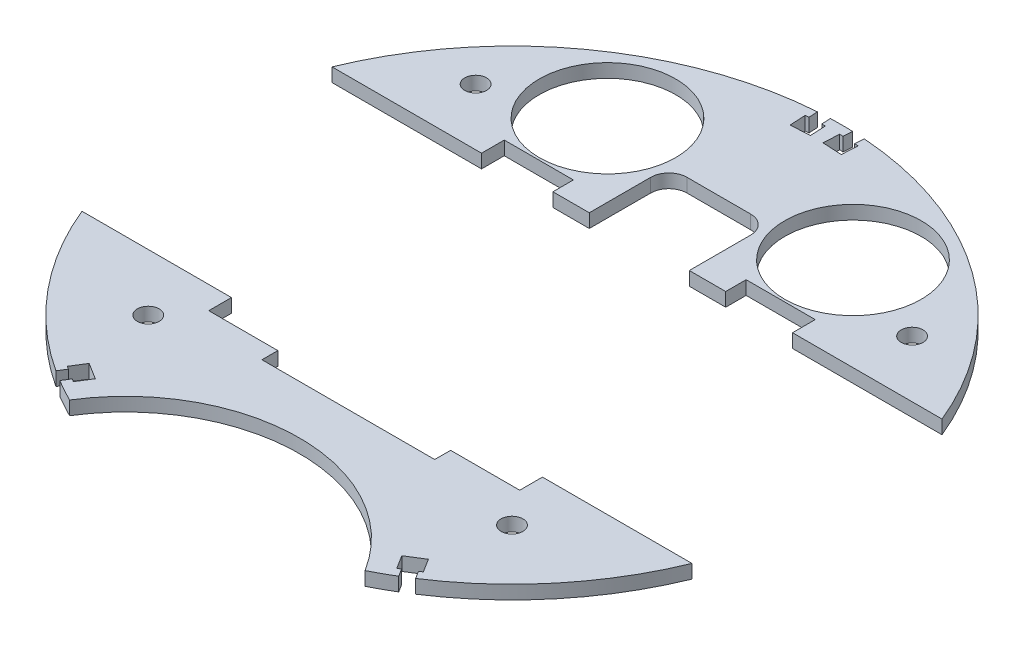
SolidWorks part; units mm, degrees
material "ABS"
ref_plane "Front Plane" through (0, 0, 0) normal (0, 0, 1) x (1, 0, 0)
ref_plane "Top Plane" through (0, 0, 0) normal (0, 1, 0) x (1, 0, 0)
ref_plane "Right Plane" through (0, 0, 0) normal (1, 0, 0) x (0, 0, -1)
sketch "Sketch1" plane through (0, 0, 0) normal (0, 1, 0) x (1, 0, 0)
  line L0 (0, -85) -> (-32.4891, -64.8129) construction
  line L1 (0, -85) -> (0, 0) construction
  arc A0 (32.4891, -64.8129) -> (-32.4891, -64.8129) centre (0, 0) ccw
  arc A1 (32.4891, -64.8129) -> (-32.4891, -64.8129) centre (0, -85) ccw
  dimension "D1" = 145
  dimension "D2" = 76.5
  dimension "D3" = 85
extrude "Boss-Extrude1" add sketch "Sketch1" along normal blind 3
sketch "solenoid placement" plane through (0, 3, 0) normal (0, 1, 0) x (1, 0, 0)
  line L4 (-19, -36) -> (19, -36)
  line L5 (-19, -36) -> (19, -36)
  line L6 (19, -36) -> (19, 28)
  line L7 (19, -36) -> (19, 28)
  line L8 (19, 28) -> (-19, 28)
  line L9 (19, 28) -> (-19, 28)
  line L10 (-19, 28) -> (-19, -36)
  line L11 (-19, 28) -> (-19, -36)
  circle A1 centre (0, 0) radius 72.5 construction
  arc A2 (32.4891, -64.8129) -> (-32.4891, -64.8129) centre (0, 0) ccw construction
  dimension "D1" = 0
extrude "Cut-Extrude1" cut sketch "solenoid placement" against normal through all
sketch "Sketch3" plane through (0, 3, 0) normal (0, 1, 0) x (1, 0, 0)
  circle A1 centre (27, 48) radius 12
  circle A2 centre (-27, 48) radius 12
  dimension "D1" = 24
extrude "Cut-Extrude3" cut sketch "Sketch3" against normal through all
sketch "Sketch4" plane through (0, 3, 0) normal (0, 1, 0) x (1, 0, 0)
  circle A2 centre (40, -40) radius 2.4
  circle A3 centre (40, -40) radius 2.4
  circle A4 centre (-40, -40) radius 2.4
  circle A5 centre (-40, -40) radius 2.4
  circle A6 centre (48, 40) radius 2.4
  circle A7 centre (48, 40) radius 2.4
  circle A8 centre (-48, 40) radius 2.4
  circle A12 centre (-48, 40) radius 2.4
  dimension "D1" = 0
  dimension "D2" = 0
  dimension "D3" = 0
  dimension "D4" = 0
extrude "Cut-Extrude4" cut sketch "Sketch4" against normal through all
sketch "Sketch2" plane through (0, 3, 0) normal (0, 1, 0) x (1, 0, 0)
  line L0 (0, 0) -> (0, 72.5) construction
  line L1 (34.2, -27.5) -> (34.2, -32.5)
  line L2 (67.082, -27.5) -> (34.2, -27.5)
  line L3 (34.2, 27.5) -> (67.082, 27.5)
  line L4 (34.2, 32.5) -> (34.2, 27.5)
  line L5 (22.2, 32.5) -> (34.2, 32.5)
  line L6 (19, 32.5) -> (22.2, 32.5)
  line L7 (19, -32.5) -> (19, 32.5)
  line L8 (22.2, -32.5) -> (19, -32.5)
  line L9 (-34.2, -32.5) -> (-22.2, -32.5)
  line L10 (-22.2, -32.5) -> (-19, -32.5)
  line L11 (-19, -32.5) -> (-19, 32.5)
  line L12 (-19, 32.5) -> (-22.2, 32.5)
  line L13 (-22.2, 32.5) -> (-34.2, 32.5)
  line L14 (-34.2, 32.5) -> (-34.2, 25)
  line L15 (-34.2, 25) -> (-68.0533, 25)
  line L16 (-68.0533, -25) -> (-34.2, -25)
  line L17 (-34.2, -25) -> (-34.2, -32.5)
  line L18 (-34.2, -32.5) -> (-22.2, -32.5)
  line L19 (-22.2, -32.5) -> (-19, -32.5)
  line L20 (-19, -32.5) -> (-19, 32.5)
  line L21 (-19, 32.5) -> (-22.2, 32.5)
  line L22 (-22.2, 32.5) -> (-34.2, 32.5)
  line L23 (-34.2, 32.5) -> (-34.2, 27.5)
  line L24 (-34.2, 27.5) -> (-67.082, 27.5)
  line L25 (-67.082, -27.5) -> (-34.2, -27.5)
  line L26 (-34.2, -27.5) -> (-34.2, -32.5)
  line L27 (34.2, -32.5) -> (22.2, -32.5)
  arc A0 (32.4891, -64.8129) -> (-32.4891, -64.8129) centre (0, 0) ccw construction
  arc A1 (67.082, 27.5) -> (67.082, -27.5) centre (0, 0) cw
  arc A2 (-68.0533, 25) -> (-68.0533, -25) centre (0, 0) ccw
  arc A3 (-67.082, 27.5) -> (-67.082, -27.5) centre (0, 0) ccw
  dimension "D2" = 55
  dimension "D1" = 0
extrude "Cut-Extrude2" cut sketch "Sketch2" against normal through all
sketch "Sketch5" plane through (0, 3, 0) normal (0, 1, 0) x (1, 0, 0)
  line L8 (-11, 28) -> (11, 28)
  line L9 (11, 28) -> (11, 41.5)
  line L10 (7, 45.5) -> (-7, 45.5)
  line L11 (-11, 41.5) -> (-11, 28)
  line L12 (19, 28) -> (-19, 28) construction
  arc A4 (11, 41.5) -> (7, 45.5) centre (7, 41.5) ccw
  arc A5 (-7, 45.5) -> (-11, 41.5) centre (-7, 41.5) ccw
  point P10 (0, 28)
  point P13 (0, 28)
  line M18 (-19, 28) -> (19, 28)
  dimension "D3" = 4
  dimension "D1" = 22
  dimension "D2" = 17.5
extrude "Cut-Extrude5" cut sketch "Sketch5" against normal through all contours L10 A5 L11 L9 A4 M18
sketch "Sketch6" plane through (0, 3, 0) normal (0, 1, 0) x (-1, 0, 0)
  circle A1 centre (-27, -48) radius 15
  circle A2 centre (-27, -48) radius 15
  circle A3 centre (27, -48) radius 15
  circle A4 centre (27, -48) radius 15
  dimension "D1" = 0
  dimension "D2" = 0
extrude "Cut-Extrude10" cut sketch "Sketch6" against normal through all
sketch "Sketch7" plane through (0, 3, 0) normal (0, 1, 0) x (1, 0, 0)
  line L8 (-5.0378, 70.3327) -> (-5.8118, 70.2922)
  line L9 (-5.8118, 70.2922) -> (-5.6286, 66.797)
  line L10 (-5.6286, 66.797) -> (-1.3844, 67.0194)
  line L11 (-1.3844, 67.0194) -> (-1.5676, 70.5146)
  line L12 (-1.5676, 70.5146) -> (-2.3415, 70.474)
  line L13 (-2.3415, 70.474) -> (-2.4462, 72.4713)
  line L14 (-2.4462, 72.4713) -> (-5.1425, 72.33)
  line L15 (-5.1425, 72.33) -> (-5.0378, 70.3327)
  line L16 (-5.0378, 70.3327) -> (-5.8118, 70.2922)
  line L17 (-5.8118, 70.2922) -> (-5.6286, 66.797)
  line L18 (-5.6286, 66.797) -> (-1.3844, 67.0194)
  line L19 (-1.3844, 67.0194) -> (-1.5676, 70.5146)
  line L20 (-1.5676, 70.5146) -> (-2.3415, 70.474)
  line L21 (-2.3415, 70.474) -> (-2.4462, 72.4713)
  line L22 (-2.4462, 72.4713) -> (-5.1425, 72.33)
  line L23 (-5.1425, 72.33) -> (-5.0378, 70.3327)
  line L24 (5.8118, 70.2922) -> (5.0378, 70.3327)
  line L25 (5.6286, 66.797) -> (5.8118, 70.2922)
  line L26 (1.3844, 67.0194) -> (5.6286, 66.797)
  line L27 (1.5676, 70.5146) -> (1.3844, 67.0194)
  line L28 (2.3415, 70.474) -> (1.5676, 70.5146)
  line L29 (2.4462, 72.4713) -> (2.3415, 70.474)
  line L30 (5.1425, 72.33) -> (2.4462, 72.4713)
  line L31 (5.0378, 70.3327) -> (5.1425, 72.33)
  line L32 (5.8118, 70.2922) -> (5.0378, 70.3327)
  line L33 (5.6286, 66.797) -> (5.8118, 70.2922)
  line L34 (1.3844, 67.0194) -> (5.6286, 66.797)
  line L35 (1.5676, 70.5146) -> (1.3844, 67.0194)
  line L36 (2.3415, 70.474) -> (1.5676, 70.5146)
  line L37 (2.4462, 72.4713) -> (2.3415, 70.474)
  line L38 (5.1425, 72.33) -> (2.4462, 72.4713)
  line L39 (5.0378, 70.3327) -> (5.1425, 72.33)
  line L40 (38.5042, -59.072) -> (39.1614, -58.6613)
  line L41 (39.564, -60.7681) -> (38.5042, -59.072)
  line L42 (37.2743, -62.1989) -> (39.564, -60.7681)
  line L43 (36.2144, -60.5028) -> (37.2743, -62.1989)
  line L44 (35.5572, -60.9135) -> (36.2144, -60.5028)
  line L45 (33.7025, -57.9453) -> (35.5572, -60.9135)
  line L46 (37.3067, -55.6931) -> (33.7025, -57.9453)
  line L47 (39.1614, -58.6613) -> (37.3067, -55.6931)
  line L48 (38.5042, -59.072) -> (39.1614, -58.6613)
  line L49 (39.564, -60.7681) -> (38.5042, -59.072)
  line L50 (37.2743, -62.1989) -> (39.564, -60.7681)
  line L51 (36.2144, -60.5028) -> (37.2743, -62.1989)
  line L52 (35.5572, -60.9135) -> (36.2144, -60.5028)
  line L53 (33.7025, -57.9453) -> (35.5572, -60.9135)
  line L54 (37.3067, -55.6931) -> (33.7025, -57.9453)
  line L55 (39.1614, -58.6613) -> (37.3067, -55.6931)
  line L56 (-39.1614, -58.6613) -> (-38.5042, -59.072)
  line L57 (-37.3067, -55.6931) -> (-39.1614, -58.6613)
  line L58 (-33.7025, -57.9453) -> (-37.3067, -55.6931)
  line L59 (-35.5572, -60.9135) -> (-33.7025, -57.9453)
  line L60 (-36.2144, -60.5028) -> (-35.5572, -60.9135)
  line L61 (-37.2743, -62.1989) -> (-36.2144, -60.5028)
  line L62 (-39.564, -60.7681) -> (-37.2743, -62.1989)
  line L63 (-38.5042, -59.072) -> (-39.564, -60.7681)
  line L64 (-39.1614, -58.6613) -> (-38.5042, -59.072)
  line L65 (-37.3067, -55.6931) -> (-39.1614, -58.6613)
  line L66 (-33.7025, -57.9453) -> (-37.3067, -55.6931)
  line L67 (-35.5572, -60.9135) -> (-33.7025, -57.9453)
  line L68 (-36.2144, -60.5028) -> (-35.5572, -60.9135)
  line L69 (-37.2743, -62.1989) -> (-36.2144, -60.5028)
  line L70 (-39.564, -60.7681) -> (-37.2743, -62.1989)
  line L71 (-38.5042, -59.072) -> (-39.564, -60.7681)
  dimension "D1" = 0
  dimension "D2" = 0
  dimension "D3" = 0
  dimension "D4" = 0
extrude "Cut-Extrude11" cut sketch "Sketch7" against normal through all
sketch "Sketch8" plane through (0, 3, 0) normal (0, 1, 0) x (1, 0, 0)
  line L2 (7, 48.5) -> (-7, 48.5)
  line L3 (7.1569, 48.5) -> (-7.1569, 48.5)
  line L8 (-8.4675, 63.6441) -> (-1.2274, 64.0235)
  line L9 (-8.8077, 70.1352) -> (-8.4675, 63.6441)
  line L10 (-6.4702, 63.7487) -> (-0.1047, 64.0823)
  line L11 (-8.6309, 66.7627) -> (-8.5721, 65.6413)
  line L15 (8.4675, 63.6441) -> (8.8077, 70.1352)
  line L16 (1.2274, 64.0235) -> (8.4675, 63.6441)
  line L17 (8.5721, 65.6413) -> (8.6309, 66.7627)
  line L18 (0.1047, 64.0823) -> (6.4702, 63.7487)
  circle A2 centre (-27, 48) radius 18
  arc A3 (-9.1412, 50.25) -> (-18.004, 63.5907) centre (-27, 48) ccw
  circle A5 centre (27, 48) radius 18
  arc A6 (18.004, 63.5907) -> (9.1412, 50.25) centre (27, 48) ccw
  arc A8 (-4.9291, 69.325) -> (-64.3062, 26.3621) centre (0, 0) ccw
  arc A9 (-10.9431, 68.6331) -> (-17.5082, 67.2585) centre (0, 0) ccw
  arc A10 (17.5082, 67.2585) -> (10.9431, 68.6331) centre (0, 0) ccw
  arc A11 (-9.1412, 50.25) -> (-7.1569, 48.5) centre (-7.1569, 50.5) ccw
  arc A12 (9.1412, 50.25) -> (7.1569, 48.5) centre (7.1569, 50.5) cw
  arc A13 (17.5082, 67.2585) -> (18.004, 63.5907) centre (17.0044, 65.323) cw
  arc A14 (10.9431, 68.6331) -> (8.6309, 66.7627) centre (10.6282, 66.658) ccw
  arc A15 (8.5721, 65.6413) -> (6.4702, 63.7487) centre (6.5749, 65.746) cw
  arc A16 (-0.1047, 64.0823) -> (0.1047, 64.0823) centre (0, 62.0851) cw
  arc A17 (-6.4702, 63.7487) -> (-8.5721, 65.6413) centre (-6.5749, 65.746) cw
  arc A18 (-8.6309, 66.7627) -> (-10.9431, 68.6331) centre (-10.6282, 66.658) ccw
  arc A19 (-18.004, 63.5907) -> (-17.5082, 67.2585) centre (-17.0044, 65.323) cw
  dimension "D5" = 2
  dimension "D1" = 3
  dimension "D2" = 3
  dimension "D3" = 3
  dimension "D4" = 3
  dimension "D6" = 3
  dimension "D7" = 3
extrude "Cut-Extrude12" [suppressed] cut sketch "Sketch8" against normal through all and the other way through all
equation "\"smallPulleyTeeth\"= 15"
equation "\"largePulleyTeeth\"= 30"
equation "\"eighthThick\"= 3.0mm"
equation "\"sixteenthThick\" = 1.7mm"
equation "\"quarterThick\"=6.0mm"
equation "\"OD\" = 145mm"
equation "\"puckAngle\" = 60.5deg"
equation "\"D1@Sketch1\"=\"OD\""
equation "\"puckDiam\" = 76.5mm"
equation "\"D2@Sketch1\"=\"puckDiam\""
equation "\"D1@Boss-Extrude1\"=\"eighthThick\""
equation "\"axlePress\" = 5.9mm"
equation "\"press\" = 0.2mm"
equation "\"wheelClear\" = 0.3mm"
equation "\"10-32clear\" = 4.8mm"
equation "\"6-32clear\" = 3.3mm"
equation "\"8-32clear\" = 4.0mm"
equation "\"wheelHeight\" = 22mm"
equation "\"wheelWell\" = 65mm"
equation "\"puckDist\" = 85mm"
equation "\"scoopFillet\" = 5mm"
equation "\"4-40clear\" = 3.0mm"
equation "\"D3@Sketch1\"=\"puckDist\""
